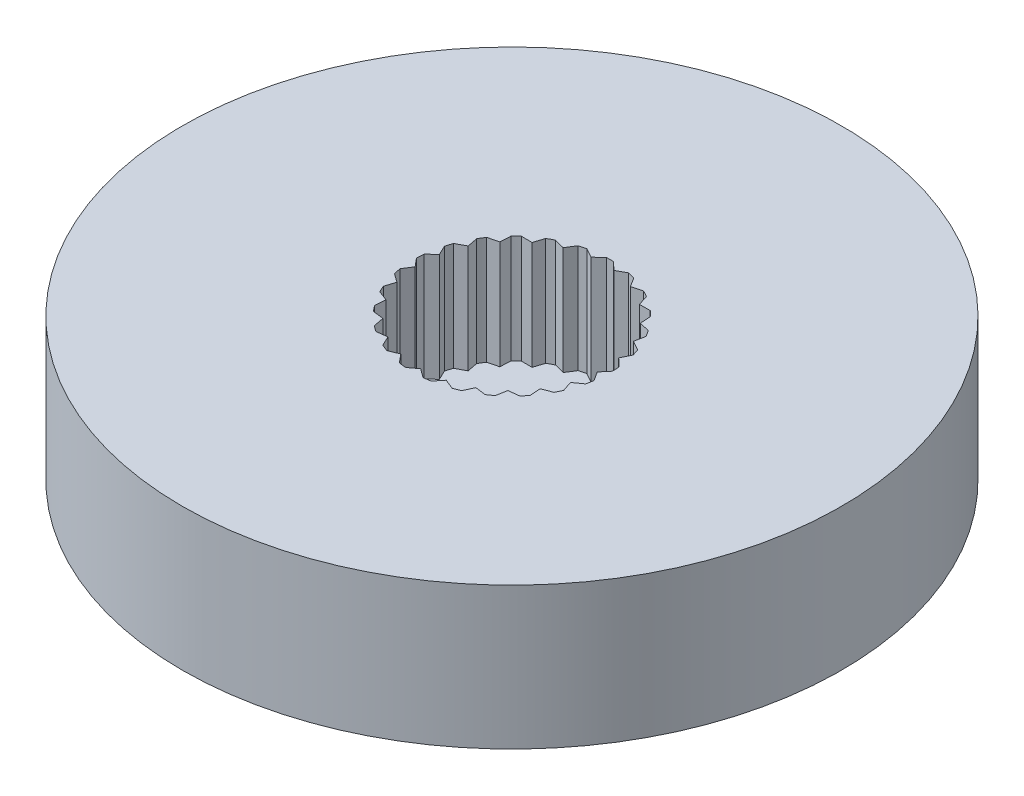
SolidWorks part; units mm, degrees
material "ABS"
ref_plane "Front Plane" through (0, 0, 0) normal (0, 0, 1) x (1, 0, 0)
ref_plane "Top Plane" through (0, 0, 0) normal (0, 1, 0) x (1, 0, 0)
ref_plane "Right Plane" through (0, 0, 0) normal (1, 0, 0) x (0, 0, -1)
sketch "Sketch2" plane through (0, 0, 0) normal (0, 1, 0) x (1, 0, 0)
  circle A0 centre (0, 0) radius 9.75
  circle A1 centre (0, 0) radius 1.5
  dimension "D1" = 19.5
  dimension "D2" = 3
extrude "Boss-Extrude1" add sketch "Sketch2" along normal mid plane 1
sketch "Sketch3" plane through (0, 0.5, 0) normal (0, 1, 0) x (1, 0, 0)
  line L0 (0, 0) -> (0, 2.9) construction
  line L3 (0, 0) -> (0.376, 2.9763) construction
  line L52 (0.1074, 2.898) -> (0.3384, 2.6787)
  line L53 (-0.1074, 2.898) -> (-0.3384, 2.6787)
  line L54 (0.8248, 2.7802) -> (0.9939, 2.5104)
  line L55 (0.6167, 2.8337) -> (0.3384, 2.6787)
  line L56 (1.4903, 2.4878) -> (1.587, 2.1843)
  line L57 (1.302, 2.5913) -> (0.9939, 2.5104)
  line L58 (2.0621, 2.039) -> (2.0804, 1.721)
  line L59 (1.9055, 2.1861) -> (1.587, 2.1843)
  line L60 (2.5044, 1.4621) -> (2.443, 1.1496)
  line L61 (2.3893, 1.6435) -> (2.0804, 1.721)
  line L62 (2.7894, 0.7934) -> (2.6522, 0.5059)
  line L63 (2.723, 0.9977) -> (2.443, 1.1496)
  line L64 (2.899, 0.0748) -> (2.6947, -0.1695)
  line L65 (2.8855, 0.2892) -> (2.6522, 0.5059)
  line L66 (2.8265, -0.6486) -> (2.5679, -0.8343)
  line L67 (2.8668, -0.4375) -> (2.6947, -0.1695)
  line L68 (2.5765, -1.3311) -> (2.2797, -1.4467)
  line L69 (2.6679, -1.1367) -> (2.5679, -0.8343)
  line L70 (2.1645, -1.93) -> (1.8483, -1.9682)
  line L71 (2.3014, -1.7645) -> (2.2797, -1.4467)
  line L72 (1.6165, -2.4077) -> (1.3007, -2.366)
  line L73 (1.7903, -2.2814) -> (1.8483, -1.9682)
  line L74 (0.967, -2.734) -> (0.6715, -2.6152)
  line L75 (1.1667, -2.655) -> (1.3007, -2.366)
  line L76 (0.2566, -2.8886) -> (0, -2.7)
  line L77 (0.4698, -2.8617) -> (0.6715, -2.6152)
  line L78 (-0.4698, -2.8617) -> (-0.6715, -2.6152)
  line L79 (-0.2566, -2.8886) -> (0, -2.7)
  line L80 (-1.1667, -2.655) -> (-1.3007, -2.366)
  line L81 (-0.967, -2.734) -> (-0.6715, -2.6152)
  line L82 (-1.7903, -2.2814) -> (-1.8483, -1.9682)
  line L83 (-1.6165, -2.4077) -> (-1.3007, -2.366)
  line L84 (-2.3014, -1.7645) -> (-2.2797, -1.4467)
  line L85 (-2.1645, -1.93) -> (-1.8483, -1.9682)
  line L86 (-2.6679, -1.1367) -> (-2.5679, -0.8343)
  line L87 (-2.5765, -1.3311) -> (-2.2797, -1.4467)
  line L88 (-2.8668, -0.4375) -> (-2.6947, -0.1695)
  line L89 (-2.8265, -0.6486) -> (-2.5679, -0.8343)
  line L90 (-2.8855, 0.2892) -> (-2.6522, 0.5059)
  line L91 (-2.899, 0.0748) -> (-2.6947, -0.1695)
  line L92 (-2.723, 0.9977) -> (-2.443, 1.1496)
  line L93 (-2.7894, 0.7934) -> (-2.6522, 0.5059)
  line L94 (-2.3893, 1.6435) -> (-2.0804, 1.721)
  line L95 (-2.5044, 1.4621) -> (-2.443, 1.1496)
  line L96 (-1.9055, 2.1861) -> (-1.587, 2.1843)
  line L97 (-2.0621, 2.039) -> (-2.0804, 1.721)
  line L98 (-1.302, 2.5913) -> (-0.9939, 2.5104)
  line L99 (-1.4903, 2.4878) -> (-1.587, 2.1843)
  line L100 (-0.6167, 2.8337) -> (-0.3384, 2.6787)
  line L101 (-0.8248, 2.7802) -> (-0.9939, 2.5104)
  line L102 (-2.533, 1.6075) -> (-2.3893, 1.6435) construction
  line L103 (-2.533, 1.6075) -> (-2.5044, 1.4621) construction
  line L104 (-2.8532, 0.9271) -> (-2.723, 0.9977) construction
  line L105 (-2.8532, 0.9271) -> (-2.7894, 0.7934) construction
  line L106 (-2.9941, 0.1884) -> (-2.8855, 0.2892) construction
  line L107 (-2.9941, 0.1884) -> (-2.899, 0.0748) construction
  line L108 (-2.9469, -0.5621) -> (-2.8668, -0.4375) construction
  line L109 (-2.9469, -0.5621) -> (-2.8265, -0.6486) construction
  line L110 (0, 3) -> (0.1074, 2.898) construction
  line L111 (0, 2.9) -> (0, 3) construction
  line L112 (0, 3) -> (-0.1074, 2.898) construction
  line L113 (-0.7461, 2.9057) -> (-0.6167, 2.8337) construction
  line L114 (-0.7461, 2.9057) -> (-0.8248, 2.7802) construction
  line L115 (-1.4453, 2.6289) -> (-1.302, 2.5913) construction
  line L116 (-1.4453, 2.6289) -> (-1.4903, 2.4878) construction
  line L117 (-2.0536, 2.1869) -> (-1.9055, 2.1861) construction
  line L118 (-2.0536, 2.1869) -> (-2.0621, 2.039) construction
  line L119 (-2.7145, -1.2773) -> (-2.6679, -1.1367) construction
  line L120 (-2.7145, -1.2773) -> (-2.5765, -1.3311) construction
  line L121 (-2.3115, -1.9123) -> (-2.3014, -1.7645) construction
  line L122 (-2.3115, -1.9123) -> (-2.1645, -1.93) construction
  line L123 (-1.7634, -2.4271) -> (-1.7903, -2.2814) construction
  line L124 (-1.7634, -2.4271) -> (-1.6165, -2.4077) construction
  line L125 (-1.1044, -2.7893) -> (-1.1667, -2.655) construction
  line L126 (-1.1044, -2.7893) -> (-0.967, -2.734) construction
  line L127 (-0.376, -2.9763) -> (-0.4698, -2.8617) construction
  line L128 (-0.376, -2.9763) -> (-0.2566, -2.8886) construction
  line L129 (0.376, -2.9763) -> (0.2566, -2.8886) construction
  line L130 (0.376, -2.9763) -> (0.4698, -2.8617) construction
  line L131 (1.1044, -2.7893) -> (0.967, -2.734) construction
  line L132 (1.1044, -2.7893) -> (1.1667, -2.655) construction
  line L133 (1.7634, -2.4271) -> (1.6165, -2.4077) construction
  line L134 (1.7634, -2.4271) -> (1.7903, -2.2814) construction
  line L135 (2.3115, -1.9123) -> (2.3014, -1.7645) construction
  line L136 (2.3115, -1.9123) -> (2.1645, -1.93) construction
  line L137 (2.7145, -1.2773) -> (2.6679, -1.1367) construction
  line L138 (2.7145, -1.2773) -> (2.5765, -1.3311) construction
  line L139 (2.9469, -0.5621) -> (2.8668, -0.4375) construction
  line L140 (2.9469, -0.5621) -> (2.8265, -0.6486) construction
  line L141 (2.9941, 0.1884) -> (2.8855, 0.2892) construction
  line L142 (2.9941, 0.1884) -> (2.899, 0.0748) construction
  line L143 (2.8532, 0.9271) -> (2.723, 0.9977) construction
  line L144 (2.8532, 0.9271) -> (2.7894, 0.7934) construction
  line L145 (2.533, 1.6075) -> (2.3893, 1.6435) construction
  line L146 (2.533, 1.6075) -> (2.5044, 1.4621) construction
  line L147 (2.0536, 2.1869) -> (1.9055, 2.1861) construction
  line L148 (2.0536, 2.1869) -> (2.0621, 2.039) construction
  line L149 (1.4453, 2.6289) -> (1.302, 2.5913) construction
  line L150 (1.4453, 2.6289) -> (1.4903, 2.4878) construction
  line L151 (0.7461, 2.9057) -> (0.6167, 2.8337) construction
  line L152 (0.7461, 2.9057) -> (0.8248, 2.7802) construction
  circle A0 centre (0, 0) radius 9.75
  circle A1 centre (0, 0) radius 3 construction
  circle A2 centre (0, 0) radius 2.7 construction
  arc A3 (-0.6167, 2.8337) -> (-0.8248, 2.7802) centre (0, 0) ccw
  arc A4 (-0.1074, 2.898) -> (-0.6167, 2.8337) centre (0, 0) ccw construction
  arc A5 (-0.8248, 2.7802) -> (-1.302, 2.5913) centre (0, 0) ccw construction
  arc A6 (-1.302, 2.5913) -> (-1.4903, 2.4878) centre (0, 0) ccw
  arc A7 (-1.4903, 2.4878) -> (-1.9055, 2.1861) centre (0, 0) ccw construction
  arc A8 (-1.9055, 2.1861) -> (-2.0621, 2.039) centre (0, 0) ccw
  arc A9 (-2.0621, 2.039) -> (-2.3893, 1.6435) centre (0, 0) ccw construction
  arc A10 (-2.3893, 1.6435) -> (-2.5044, 1.4621) centre (0, 0) ccw
  arc A11 (-2.5044, 1.4621) -> (-2.723, 0.9977) centre (0, 0) ccw construction
  arc A12 (-2.723, 0.9977) -> (-2.7894, 0.7934) centre (0, 0) ccw
  arc A13 (-2.7894, 0.7934) -> (-2.8855, 0.2892) centre (0, 0) ccw construction
  arc A14 (-2.8855, 0.2892) -> (-2.899, 0.0748) centre (0, 0) ccw
  arc A15 (-2.899, 0.0748) -> (-2.8668, -0.4375) centre (0, 0) ccw construction
  arc A16 (-2.8668, -0.4375) -> (-2.8265, -0.6486) centre (0, 0) ccw
  arc A17 (-2.8265, -0.6486) -> (-2.6679, -1.1367) centre (0, 0) ccw construction
  arc A18 (-2.6679, -1.1367) -> (-2.5765, -1.3311) centre (0, 0) ccw
  arc A19 (-2.5765, -1.3311) -> (-2.3014, -1.7645) centre (0, 0) ccw construction
  arc A20 (-2.3014, -1.7645) -> (-2.1645, -1.93) centre (0, 0) ccw
  arc A21 (-2.1645, -1.93) -> (-1.7903, -2.2814) centre (0, 0) ccw construction
  arc A22 (-1.7903, -2.2814) -> (-1.6165, -2.4077) centre (0, 0) ccw
  arc A23 (-1.6165, -2.4077) -> (-1.1667, -2.655) centre (0, 0) ccw construction
  arc A24 (-1.1667, -2.655) -> (-0.967, -2.734) centre (0, 0) ccw
  arc A25 (-0.967, -2.734) -> (-0.4698, -2.8617) centre (0, 0) ccw construction
  arc A26 (-0.4698, -2.8617) -> (-0.2566, -2.8886) centre (0, 0) ccw
  arc A27 (-0.2566, -2.8886) -> (0.2566, -2.8886) centre (0, 0) ccw construction
  arc A28 (0.2566, -2.8886) -> (0.4698, -2.8617) centre (0, 0) ccw
  arc A29 (0.4698, -2.8617) -> (0.967, -2.734) centre (0, 0) ccw construction
  arc A30 (0.967, -2.734) -> (1.1667, -2.655) centre (0, 0) ccw
  arc A31 (1.1667, -2.655) -> (1.6165, -2.4077) centre (0, 0) ccw construction
  arc A32 (1.6165, -2.4077) -> (1.7903, -2.2814) centre (0, 0) ccw
  arc A33 (1.7903, -2.2814) -> (2.1645, -1.93) centre (0, 0) ccw construction
  arc A34 (2.1645, -1.93) -> (2.3014, -1.7645) centre (0, 0) ccw
  arc A35 (2.3014, -1.7645) -> (2.5765, -1.3311) centre (0, 0) ccw construction
  arc A36 (2.5765, -1.3311) -> (2.6679, -1.1367) centre (0, 0) ccw
  arc A37 (2.6679, -1.1367) -> (2.8265, -0.6486) centre (0, 0) ccw construction
  arc A38 (2.8265, -0.6486) -> (2.8668, -0.4375) centre (0, 0) ccw
  arc A39 (2.8668, -0.4375) -> (2.899, 0.0748) centre (0, 0) ccw construction
  arc A40 (2.899, 0.0748) -> (2.8855, 0.2892) centre (0, 0) ccw
  arc A41 (2.8855, 0.2892) -> (2.7894, 0.7934) centre (0, 0) ccw construction
  arc A42 (2.7894, 0.7934) -> (2.723, 0.9977) centre (0, 0) ccw
  arc A43 (2.723, 0.9977) -> (2.5044, 1.4621) centre (0, 0) ccw construction
  arc A44 (2.5044, 1.4621) -> (2.3893, 1.6435) centre (0, 0) ccw
  arc A45 (2.3893, 1.6435) -> (2.0621, 2.039) centre (0, 0) ccw construction
  arc A46 (2.0621, 2.039) -> (1.9055, 2.1861) centre (0, 0) ccw
  arc A47 (1.9055, 2.1861) -> (1.4903, 2.4878) centre (0, 0) ccw construction
  arc A48 (1.4903, 2.4878) -> (1.302, 2.5913) centre (0, 0) ccw
  arc A49 (1.302, 2.5913) -> (0.8248, 2.7802) centre (0, 0) ccw construction
  arc A50 (0.8248, 2.7802) -> (0.6167, 2.8337) centre (0, 0) ccw
  arc A51 (0.3635, 2.8771) -> (0.1074, 2.898) centre (0, 0) ccw construction
  arc A52 (0.1074, 2.898) -> (-0.1074, 2.898) centre (0, 0) ccw
  arc A53 (0.6167, 2.8337) -> (0.3635, 2.8771) centre (0, 0) ccw construction
  point P84 (0, 0)
  dimension "19.5" = 19.5
  dimension "D2" = 5.4
  dimension "D3" = 6
  dimension "D6" = 5.8
  dimension "D4" = 7.2
  dimension "D5" = 25
extrude "Boss-Extrude2" add sketch "Sketch3" along normal blind 3.2
sketch "Sketch4" plane through (0, 0, 0) normal (0, 1, 0) x (1, 0, 0)
  line L0 (0, 0) -> (13, 0) construction
  line L1 (8.6494, 4.5) -> (14.3818, 2.3393)
  line L2 (8.6494, -4.5) -> (14.3818, -2.3393)
  line L3 (13, 0) -> (10, 0) construction
  circle A0 centre (0, 0) radius 9.75 construction
  arc A1 (8.6494, -4.5) -> (8.6494, 4.5) centre (0, 0) ccw
  arc A2 (14.3818, 2.3393) -> (14.3818, -2.3393) centre (13.5, 0) cw
  circle A3 centre (13, 0) radius 0.75
  circle A4 centre (10, 0) radius 0.75
  circle A5 centre (7, 0) radius 0.75
  dimension "D3" = 2.5
  dimension "D5" = 1.5
  dimension "D2" = 9
  dimension "D7" = 3
  dimension "D4" = 0.5
  dimension "D1" = 13
  dimension "D6" = 3
extrude "Boss-Extrude3" [suppressed] add sketch "Sketch4" along normal mid plane 2.3
pattern_circular "CirPattern1" [suppressed] count 6 over 360
sketch "Sketch5" plane through (0, 0, 0) normal (0, 1, 0) x (1, 0, 0)
  line L0 (3, 7) -> (-3, 7) construction
  circle A0 centre (0, 0) radius 11
  circle A13 centre (0, 0) radius 1.5 construction
  circle A14 centre (0, 0) radius 1.5
  point P8 (0, 7)
  point P31 (0, 0)
  dimension "D1" = 22
  dimension "D4" = 6
equation "\"N_hole\"= 3"
equation "\"N_horn\"= 6"
equation "\"D6@Sketch4\"=\"N_hole\""
equation "\"D1@CirPattern1\"=\"N_horn\""
equation "\"D1@Sketch4\"=(\"N_hole\" - 1) *3 +7"
